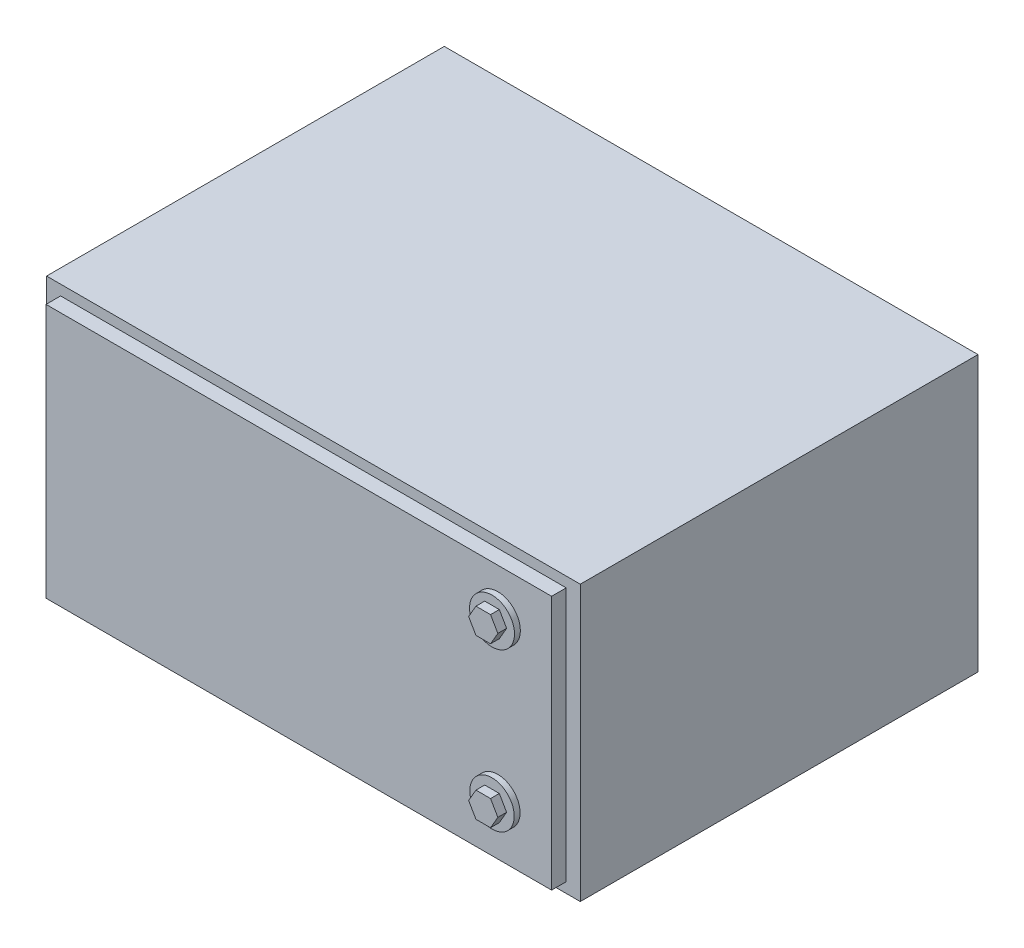
SolidWorks part; units mm, degrees
material "ABS"
ref_plane "Front Plane" through (0, 0, 0) normal (0, 0, 1) x (1, 0, 0)
ref_plane "Top Plane" through (0, 0, 0) normal (0, 1, 0) x (1, 0, 0)
ref_plane "Right Plane" through (0, 0, 0) normal (1, 0, 0) x (0, 0, -1)
sketch "Sketch2" plane through (0, 0, 0) normal (0, 0, 1) x (1, 0, 0)
  line L1 (-182.5, 94) -> (182.5, 94)
  line L2 (-182.5, 94) -> (-182.5, -94)
  line L3 (-182.5, -94) -> (182.5, -94)
  line L4 (182.5, 94) -> (182.5, -94)
  line L5 (-182.5, 94) -> (182.5, -94) construction
  line L6 (-182.5, -94) -> (182.5, 94) construction
  point P0 (0, 0)
  dimension "D1" = 365
  dimension "D2" = 188
extrude "Boss-Extrude1" add sketch "Sketch2" along normal blind 272
sketch "Sketch3" plane through (0, 0, 272) normal (0, 0, 1) x (1, 0, 0)
  line L1 (-172.8874, 87.0226) -> (172.8874, 87.0226)
  line L2 (-172.8874, 87.0226) -> (-172.8874, -87.0226)
  line L3 (-172.8874, -87.0226) -> (172.8874, -87.0226)
  line L4 (172.8874, 87.0226) -> (172.8874, -87.0226)
  line L5 (-172.8874, 87.0226) -> (172.8874, -87.0226) construction
  line L6 (-172.8874, -87.0226) -> (172.8874, 87.0226) construction
  point P0 (0, 0)
extrude "Boss-Extrude2" add sketch "Sketch3" along normal blind 10
sketch "Sketch4" plane through (0, 0, 282) normal (0, 0, 1) x (1, 0, 0)
  line L0 (136.1412, 87.0226) -> (136.1412, -87.0226) construction
  line L1 (172.8874, 87.0226) -> (-172.8874, 87.0226) construction
  line L2 (-172.8874, -87.0226) -> (172.8874, -87.0226) construction
  line L10 (146.1269, 56.6425) -> (141.1341, 65.2904)
  line L11 (141.1341, 65.2904) -> (131.1484, 65.2904)
  line L12 (131.1484, 65.2904) -> (126.1556, 56.6425)
  line L13 (126.1556, 56.6425) -> (131.1484, 47.9947)
  line L14 (131.1484, 47.9947) -> (141.1341, 47.9947)
  line L15 (141.1341, 47.9947) -> (146.1269, 56.6425)
  line L16 (146.1269, -52.2895) -> (141.1341, -43.6417)
  line L17 (141.1341, -43.6417) -> (131.1484, -43.6417)
  line L18 (131.1484, -43.6417) -> (126.1556, -52.2895)
  line L19 (126.1556, -52.2895) -> (131.1484, -60.9374)
  line L20 (131.1484, -60.9374) -> (141.1341, -60.9374)
  line L21 (141.1341, -60.9374) -> (146.1269, -52.2895)
  circle A0 centre (136.1412, 56.6425) radius 8.6478 construction
  circle A1 centre (136.1412, -52.2895) radius 8.6478 construction
extrude "Boss-Extrude3" add sketch "Sketch4" along normal blind 10
sketch "Sketch5" plane through (0, 0, 282) normal (0, 0, 1) x (1, 0, 0)
  circle A0 centre (136.1412, 56.004) radius 15.3723
  circle A1 centre (136.1412, -52.0416) radius 15.1862
extrude "Boss-Extrude4" add sketch "Sketch5" along normal blind 4
